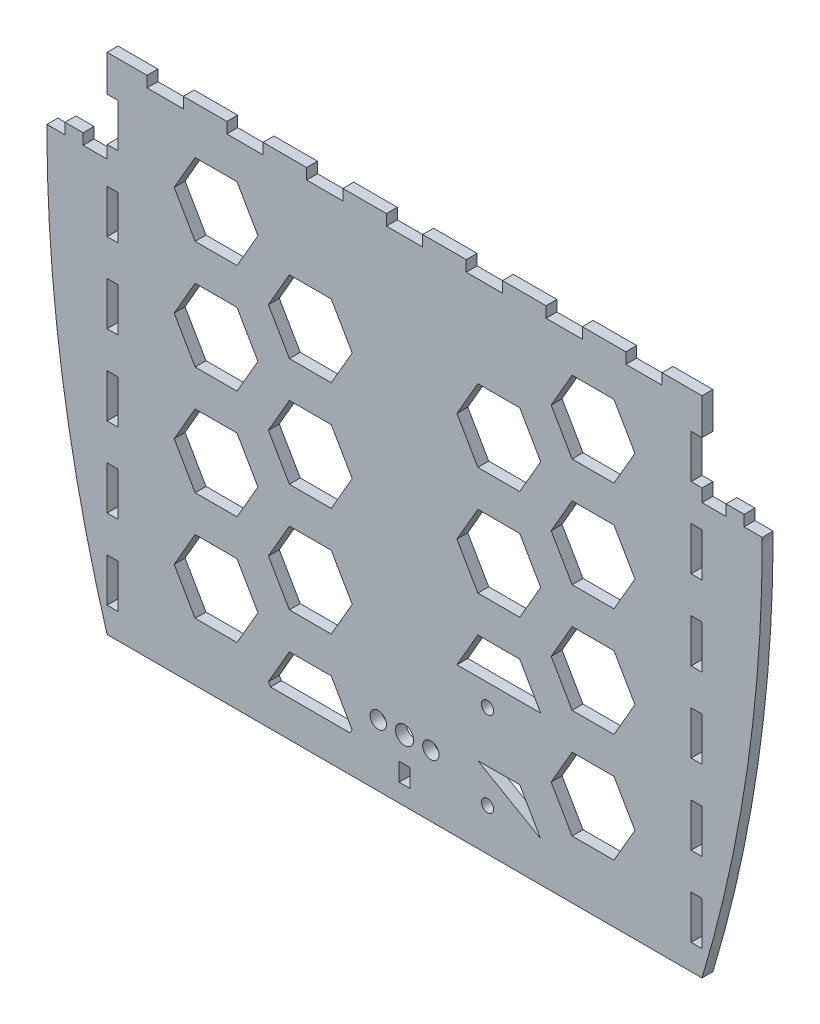
SolidWorks part; units mm, degrees
material "birch 3mm plywood"
ref_plane "Front Plane" through (0, 0, 0) normal (0, 0, 1) x (1, 0, 0)
ref_plane "Top Plane" through (0, 0, 0) normal (0, 1, 0) x (1, 0, 0)
ref_plane "Right Plane" through (0, 0, 0) normal (1, 0, 0) x (0, 0, -1)
sketch "Sketch1" plane through (0, 0, 152) normal (0, 0, 1) x (1, 0, 0)
  line L1 (-82, 69.5) -> (82, 69.5)
  line L2 (-82, 69.5) -> (-82, 44)
  line L3 (-82, -69.5) -> (82, -69.5)
  line L4 (82, 69.5) -> (82, 44)
  line L8 (-88.6, 47) -> (-93.6, 47)
  line L9 (-98.6, 44) -> (-98.6, 43.3771)
  line L12 (75, -62.5) -> (-75, -62.5) construction
  line L13 (75, 62.5) -> (75, -62.5) construction
  line L14 (-75, -62.5) -> (-75, 62.5) construction
  line L15 (-75, 62.5) -> (75, 62.5) construction
  line L33 (-93.6, 47) -> (-93.6, 44)
  line L34 (-93.6, 44) -> (-98.6, 44)
  line L35 (-88.6, 47) -> (-88.6, 44)
  line L36 (-88.6, 44) -> (-82, 44)
  line L37 (98.6, 44) -> (98.6, 43.3771)
  line L38 (93.6, 44) -> (98.6, 44)
  line L39 (93.6, 47) -> (93.6, 44)
  line L40 (88.6, 47) -> (93.6, 47)
  line L41 (88.6, 47) -> (88.6, 44)
  line L42 (88.6, 44) -> (82, 44)
  arc A12 (-98.6, 43.3771) -> (-82, -69.5) centre (293.4723, 43.3771) ccw
  arc A14 (98.6, 43.3771) -> (82, -69.5) centre (-293.4723, 43.3771) cw
  dimension "D3" = 7
  dimension "D11" = 150
  dimension "D12" = 125
  dimension "D13" = 7
  dimension "D14" = 22.5
  dimension "D15" = 16.6
  dimension "D16" = 3
  dimension "D17" = 5
  dimension "D18" = 5
extrude "Boss-Extrude1" add sketch "Sketch1" along normal blind 3
sketch "Sketch2" plane through (0, 0, 155) normal (0, 0, 1) x (1, 0, 0)
  line L0 (0, 69.5) -> (0, -69.5) construction
  line L1 (17, 69.5) -> (17, 66.5)
  line L2 (-5, 69.5) -> (5, 69.5)
  line L3 (-5, 69.5) -> (-5, 66.5)
  line L4 (-82, 69.5) -> (-82, 44)
  line L5 (-82, -69.5) -> (82, -69.5)
  line L6 (82, 44) -> (82, 69.5)
  line L7 (82, 69.5) -> (-82, 69.5)
  line L8 (-82, 69.5) -> (-82, 44)
  line L9 (-82, -69.5) -> (82, -69.5)
  line L10 (82, 44) -> (82, 69.5)
  line L11 (82, 69.5) -> (-82, 69.5)
  line L12 (-5, 66.5) -> (5, 66.5)
  line L13 (5, 69.5) -> (5, 66.5)
  line L14 (17, 69.5) -> (27, 69.5)
  line L15 (27, 69.5) -> (27, 66.5)
  line L16 (17, 66.5) -> (27, 66.5)
  line L17 (39, 69.5) -> (39, 66.5)
  line L18 (39, 69.5) -> (49, 69.5)
  line L19 (49, 69.5) -> (49, 66.5)
  line L20 (39, 66.5) -> (49, 66.5)
  line L21 (61, 69.5) -> (61, 66.5)
  line L22 (61, 69.5) -> (71, 69.5)
  line L23 (71, 69.5) -> (71, 66.5)
  line L24 (61, 66.5) -> (71, 66.5)
  line L25 (-27, 69.5) -> (-27, 66.5)
  line L26 (-27, 69.5) -> (-17, 69.5)
  line L27 (-17, 69.5) -> (-17, 66.5)
  line L28 (-27, 66.5) -> (-17, 66.5)
  line L29 (-49, 69.5) -> (-49, 66.5)
  line L30 (-49, 69.5) -> (-39, 69.5)
  line L31 (-39, 69.5) -> (-39, 66.5)
  line L32 (-49, 66.5) -> (-39, 66.5)
  line L33 (-71, 69.5) -> (-71, 66.5)
  line L34 (-71, 69.5) -> (-61, 69.5)
  line L35 (-61, 69.5) -> (-61, 66.5)
  line L36 (-71, 66.5) -> (-61, 66.5)
  line L37 (-82, 37.5) -> (-82, 25.5)
  line L38 (-82, 59.5) -> (-79, 59.5)
  line L39 (-82, 59.5) -> (-82, 47.5)
  line L40 (-82, 47.5) -> (-79, 47.5)
  line L41 (-79, 59.5) -> (-79, 47.5)
  line L42 (-82, 37.5) -> (-79, 37.5)
  line L43 (-79, 37.5) -> (-79, 25.5)
  line L44 (-82, 25.5) -> (-79, 25.5)
  line L45 (-82, 15.5) -> (-82, 3.5)
  line L46 (-82, 15.5) -> (-79, 15.5)
  line L47 (-79, 15.5) -> (-79, 3.5)
  line L48 (-82, 3.5) -> (-79, 3.5)
  line L49 (-82, -6.5) -> (-82, -18.5)
  line L50 (-82, -6.5) -> (-79, -6.5)
  line L51 (-79, -6.5) -> (-79, -18.5)
  line L52 (-82, -18.5) -> (-79, -18.5)
  line L53 (-82, -28.5) -> (-82, -40.5)
  line L54 (-82, -28.5) -> (-79, -28.5)
  line L55 (-79, -28.5) -> (-79, -40.5)
  line L56 (-82, -40.5) -> (-79, -40.5)
  line L57 (-82, -50.5) -> (-82, -62.5)
  line L58 (-82, -50.5) -> (-79, -50.5)
  line L59 (-79, -50.5) -> (-79, -62.5)
  line L60 (-82, -62.5) -> (-79, -62.5)
  line L65 (82, -50.5) -> (79, -50.5)
  line L66 (79, -50.5) -> (79, -62.5)
  line L67 (82, -62.5) -> (79, -62.5)
  line L68 (82, -50.5) -> (82, -62.5)
  line L69 (82, -28.5) -> (79, -28.5)
  line L70 (79, -28.5) -> (79, -40.5)
  line L71 (82, -40.5) -> (79, -40.5)
  line L72 (82, -28.5) -> (82, -40.5)
  line L73 (82, -6.5) -> (79, -6.5)
  line L74 (79, -6.5) -> (79, -18.5)
  line L75 (82, -18.5) -> (79, -18.5)
  line L76 (82, -6.5) -> (82, -18.5)
  line L77 (82, 15.5) -> (79, 15.5)
  line L78 (79, 15.5) -> (79, 3.5)
  line L79 (82, 3.5) -> (79, 3.5)
  line L80 (82, 15.5) -> (82, 3.5)
  line L81 (82, 37.5) -> (79, 37.5)
  line L82 (79, 37.5) -> (79, 25.5)
  line L83 (82, 25.5) -> (79, 25.5)
  line L84 (82, 37.5) -> (82, 25.5)
  line L85 (82, 47.5) -> (79, 47.5)
  line L86 (79, 59.5) -> (79, 47.5)
  line L87 (82, 59.5) -> (79, 59.5)
  line L88 (82, 59.5) -> (82, 47.5)
  line L97 (-88.6, 47) -> (-93.6, 47)
  line L98 (-88.6, 47) -> (-93.6, 47)
  line L99 (-98.6, 44) -> (-98.6, 43.3771)
  line L100 (-98.6, 44) -> (-98.6, 43.3771)
  line L101 (98.6, 43.3771) -> (98.6, 44)
  line L103 (98.6, 43.3771) -> (98.6, 44)
  line L109 (-82, 44) -> (-88.6, 44)
  line L110 (-82, 44) -> (-88.6, 44)
  line L111 (-88.6, 44) -> (-88.6, 47)
  line L112 (-88.6, 44) -> (-88.6, 47)
  line L113 (-93.6, 47) -> (-93.6, 44)
  line L114 (-93.6, 47) -> (-93.6, 44)
  line L115 (-93.6, 44) -> (-98.6, 44)
  line L116 (-93.6, 44) -> (-98.6, 44)
  line L121 (98.6, 44) -> (93.6, 44)
  line L122 (98.6, 44) -> (93.6, 44)
  line L123 (93.6, 44) -> (93.6, 47)
  line L124 (93.6, 44) -> (93.6, 47)
  line L125 (93.6, 47) -> (88.6, 47)
  line L126 (93.6, 47) -> (88.6, 47)
  line L127 (88.6, 47) -> (88.6, 44)
  line L128 (88.6, 47) -> (88.6, 44)
  line L129 (88.6, 44) -> (82, 44)
  line L130 (88.6, 44) -> (82, 44)
  arc A2 (-98.6, 43.3771) -> (-82, -69.5) centre (293.4723, 43.3771) ccw
  arc A3 (-98.6, 43.3771) -> (-82, -69.5) centre (293.4723, 43.3771) ccw
  arc A4 (82, -69.5) -> (98.6, 43.3771) centre (-293.4723, 43.3771) ccw
  arc A6 (82, -69.5) -> (98.6, 43.3771) centre (-293.4723, 43.3771) ccw
  point P10 (0, 66.5)
  line M64 (82, 44) -> (82, 69.5)
  line M65 (82, 69.5) -> (-82, 69.5)
  dimension "D2" = 10
  dimension "D3" = 3
  dimension "D6" = 12
  dimension "D7" = 12
  dimension "D8" = 3
  dimension "D9" = 12
  dimension "D10" = 10
  dimension "D12" = 10
  dimension "D1" = 0
  dimension "D4" = 4
  dimension "D5" = 4
  dimension "D11" = 6
extrude "Cut-Extrude1" cut sketch "Sketch2" against normal blind 10 contours L8 L44 L43 L42 | L33 L36 L35 L11 | L29 L32 L31 M65 | L25 L28 L27 L11 | L0 L12 L13 M65 | L0 L11 L3 L12 | L1 L16 L15 L11 | L17 L20 L19 L11 | L21 L24 L23 L11 | L87 L86 L85 M64 | L79 L77 L78 M64 | L75 L10 L73 L74 | L71 L69 L70 M64 | L67 L10 L65 L66 | L41 L40 L39 L38 | L47 L48 L45 L46 | L51 L52 L49 L50 | L55 L56 L53 L54 | L59 L60 L57 L58 | L82 L83 L84 L81
sketch "Sketch3" plane through (0, 0, 155) normal (0, 0, 1) x (1, 0, 0)
  line L0 (-49, 66.5) -> (-39, 66.5) construction
  line L1 (-45.906, 46.5) -> (-51.6795, 56.5)
  line L2 (-51.6795, 56.5) -> (-63.2265, 56.5)
  line L3 (-63.2265, 56.5) -> (-69, 46.5)
  line L4 (-69, 46.5) -> (-63.2265, 36.5)
  line L5 (-63.2265, 36.5) -> (-51.6795, 36.5)
  line L6 (-51.6795, 36.5) -> (-45.906, 46.5)
  line L7 (-79, 37.5) -> (-79, 25.5) construction
  line L8 (-19.9252, 31.5) -> (-25.6987, 41.5)
  line L9 (-25.6987, 41.5) -> (-37.2457, 41.5)
  line L10 (-37.2457, 41.5) -> (-43.0192, 31.5)
  line L11 (-43.0192, 31.5) -> (-37.2457, 21.5)
  line L12 (-37.2457, 21.5) -> (-25.6987, 21.5)
  line L13 (-25.6987, 21.5) -> (-19.9252, 31.5)
  line L16 (-13.2265, 56.5) -> (-19, 46.5)
  line L17 (-19, 46.5) -> (-13.2265, 36.5)
  line L18 (-13.2265, 36.5) -> (-10, 36.5)
  line L20 (30.0748, 31.5) -> (24.3013, 41.5)
  line L21 (24.3013, 41.5) -> (12.7543, 41.5)
  line L22 (12.7543, 41.5) -> (10, 36.7295)
  line L23 (10, 26.2705) -> (12.7543, 21.5)
  line L24 (12.7543, 21.5) -> (24.3013, 21.5)
  line L25 (24.3013, 21.5) -> (30.0748, 31.5)
  line L26 (54.094, 46.5) -> (48.3205, 56.5)
  line L27 (48.3205, 56.5) -> (36.7735, 56.5)
  line L28 (36.7735, 56.5) -> (31, 46.5)
  line L29 (31, 46.5) -> (36.7735, 36.5)
  line L30 (36.7735, 36.5) -> (48.3205, 36.5)
  line L31 (48.3205, 36.5) -> (54.094, 46.5)
  line L33 (68.5278, 41.5) -> (62.7543, 41.5)
  line L34 (62.7543, 41.5) -> (56.9808, 31.5)
  line L35 (56.9808, 31.5) -> (62.7543, 21.5)
  line L36 (62.7543, 21.5) -> (68.5278, 21.5)
  line L39 (-10, 26.5) -> (-13.2265, 26.5)
  line L40 (-13.2265, 26.5) -> (-19, 16.5)
  line L41 (-19, 16.5) -> (-13.2265, 6.5)
  line L42 (-13.2265, 6.5) -> (-10, 6.5)
  line L44 (30.0748, 1.5) -> (24.3013, 11.5)
  line L45 (24.3013, 11.5) -> (12.7543, 11.5)
  line L46 (12.7543, 11.5) -> (10, 6.7295)
  line L47 (10, -3.7295) -> (12.7543, -8.5)
  line L48 (12.7543, -8.5) -> (24.3013, -8.5)
  line L49 (24.3013, -8.5) -> (30.0748, 1.5)
  line L50 (54.094, 16.5) -> (48.3205, 26.5)
  line L51 (48.3205, 26.5) -> (36.7735, 26.5)
  line L52 (36.7735, 26.5) -> (31, 16.5)
  line L53 (31, 16.5) -> (36.7735, 6.5)
  line L54 (36.7735, 6.5) -> (48.3205, 6.5)
  line L55 (48.3205, 6.5) -> (54.094, 16.5)
  line L57 (68.5278, 11.5) -> (62.7543, 11.5)
  line L58 (62.7543, 11.5) -> (56.9808, 1.5)
  line L59 (56.9808, 1.5) -> (62.7543, -8.5)
  line L60 (62.7543, -8.5) -> (68.5278, -8.5)
  line L64 (-13.2265, -3.5) -> (-19, -13.5)
  line L65 (-19, -13.5) -> (-13.2265, -23.5)
  line L66 (-13.2265, -23.5) -> (-10, -23.5)
  line L68 (30.0748, -28.5) -> (24.3013, -18.5)
  line L69 (24.3013, -18.5) -> (12.7543, -18.5)
  line L70 (12.7543, -18.5) -> (10, -23.2705)
  line L71 (10, -33.7295) -> (12.7543, -38.5)
  line L72 (12.7543, -38.5) -> (24.3013, -38.5)
  line L73 (24.3013, -38.5) -> (30.0748, -28.5)
  line L74 (54.094, -13.5) -> (48.3205, -3.5)
  line L75 (48.3205, -3.5) -> (36.7735, -3.5)
  line L76 (36.7735, -3.5) -> (31, -13.5)
  line L77 (31, -13.5) -> (36.7735, -23.5)
  line L78 (36.7735, -23.5) -> (48.3205, -23.5)
  line L79 (48.3205, -23.5) -> (54.094, -13.5)
  line L81 (68.5278, -18.5) -> (62.7543, -18.5)
  line L82 (62.7543, -18.5) -> (56.9808, -28.5)
  line L83 (56.9808, -28.5) -> (62.7543, -38.5)
  line L84 (62.7543, -38.5) -> (68.5278, -38.5)
  line L88 (-13.2265, -33.5) -> (-19, -43.5)
  line L89 (-19, -43.5) -> (-13.2265, -53.5)
  line L90 (-13.2265, -53.5) -> (-10, -53.5)
  line L92 (30.0748, -58.5) -> (24.3013, -48.5)
  line L93 (24.3013, -48.5) -> (12.7543, -48.5)
  line L94 (12.7543, -48.5) -> (10, -53.2705)
  line L98 (54.094, -43.5) -> (48.3205, -33.5)
  line L99 (48.3205, -33.5) -> (36.7735, -33.5)
  line L100 (36.7735, -33.5) -> (31, -43.5)
  line L101 (31, -43.5) -> (36.7735, -53.5)
  line L102 (36.7735, -53.5) -> (48.3205, -53.5)
  line L103 (48.3205, -53.5) -> (54.094, -43.5)
  line L105 (68.5278, -48.5) -> (62.7543, -48.5)
  line L106 (62.7543, -48.5) -> (56.9808, -58.5)
  line L134 (-45.906, 16.5) -> (-51.6795, 26.5)
  line L135 (-51.6795, 26.5) -> (-63.2265, 26.5)
  line L136 (-63.2265, 26.5) -> (-69, 16.5)
  line L137 (-69, 16.5) -> (-63.2265, 6.5)
  line L138 (-63.2265, 6.5) -> (-51.6795, 6.5)
  line L139 (-51.6795, 6.5) -> (-45.906, 16.5)
  line L140 (-19.9252, 1.5) -> (-25.6987, 11.5)
  line L141 (-25.6987, 11.5) -> (-37.2457, 11.5)
  line L142 (-37.2457, 11.5) -> (-43.0192, 1.5)
  line L143 (-43.0192, 1.5) -> (-37.2457, -8.5)
  line L144 (-37.2457, -8.5) -> (-25.6987, -8.5)
  line L145 (-25.6987, -8.5) -> (-19.9252, 1.5)
  line L146 (-45.906, -13.5) -> (-51.6795, -3.5)
  line L147 (-51.6795, -3.5) -> (-63.2265, -3.5)
  line L148 (-63.2265, -3.5) -> (-69, -13.5)
  line L149 (-69, -13.5) -> (-63.2265, -23.5)
  line L150 (-63.2265, -23.5) -> (-51.6795, -23.5)
  line L151 (-51.6795, -23.5) -> (-45.906, -13.5)
  line L152 (-19.9252, -28.5) -> (-25.6987, -18.5)
  line L153 (-25.6987, -18.5) -> (-37.2457, -18.5)
  line L154 (-37.2457, -18.5) -> (-43.0192, -28.5)
  line L155 (-43.0192, -28.5) -> (-37.2457, -38.5)
  line L156 (-37.2457, -38.5) -> (-25.6987, -38.5)
  line L157 (-25.6987, -38.5) -> (-19.9252, -28.5)
  line L158 (-45.906, -43.5) -> (-51.6795, -33.5)
  line L159 (-51.6795, -33.5) -> (-63.2265, -33.5)
  line L160 (-63.2265, -33.5) -> (-69, -43.5)
  line L161 (-69, -43.5) -> (-63.2265, -53.5)
  line L162 (-63.2265, -53.5) -> (-51.6795, -53.5)
  line L163 (-51.6795, -53.5) -> (-45.906, -43.5)
  line L164 (-19.9252, -58.5) -> (-25.6987, -48.5)
  line L165 (-25.6987, -48.5) -> (-37.2457, -48.5)
  line L166 (-37.2457, -48.5) -> (-43.0192, -58.5)
  line L185 (-40, 56.5) -> (-37.2457, 51.7295)
  line L186 (-37.2457, 51.7295) -> (-25.6987, 51.7295)
  line L187 (-25.6987, 51.7295) -> (-22.9445, 56.5)
  line L188 (31, -73.5) -> (36.7735, -83.5) [skipped]
  line L189 (36.7735, -83.5) -> (48.3205, -83.5) [skipped]
  line L190 (48.3205, -83.5) -> (54.094, -73.5) [skipped]
  line L191 (80.0748, -88.5) -> (74.3013, -78.5) [skipped]
  line L192 (74.3013, -78.5) -> (62.7543, -78.5) [skipped]
  line L193 (62.7543, -78.5) -> (56.9808, -88.5) [skipped]
  line L194 (56.9808, -88.5) -> (62.7543, -98.5) [skipped]
  line L195 (62.7543, -98.5) -> (74.3013, -98.5) [skipped]
  line L196 (74.3013, -98.5) -> (80.0748, -88.5) [skipped]
  line L197 (54.094, -73.5) -> (48.3205, -63.5) [skipped]
  line L198 (48.3205, -63.5) -> (36.7735, -63.5) [skipped]
  line L199 (36.7735, -63.5) -> (31, -73.5) [skipped]
  line L200 (-1.6795, -83.5) -> (4.094, -73.5) [skipped]
  line L201 (30.0748, -88.5) -> (24.3013, -78.5) [skipped]
  line L202 (24.3013, -78.5) -> (12.7543, -78.5) [skipped]
  line L203 (12.7543, -78.5) -> (6.9808, -88.5) [skipped]
  line L204 (6.9808, -88.5) -> (12.7543, -98.5) [skipped]
  line L205 (12.7543, -98.5) -> (24.3013, -98.5) [skipped]
  line L206 (24.3013, -98.5) -> (30.0748, -88.5) [skipped]
  line L207 (4.094, -73.5) -> (-1.6795, -63.5) [skipped]
  line L208 (-1.6795, -63.5) -> (-13.2265, -63.5) [skipped]
  line L209 (-13.2265, -63.5) -> (-19, -73.5) [skipped]
  line L210 (-19, -73.5) -> (-13.2265, -83.5) [skipped]
  line L211 (-13.2265, -83.5) -> (-1.6795, -83.5) [skipped]
  line L212 (-19.9252, -88.5) -> (-25.6987, -78.5) [skipped]
  line L213 (-25.6987, -78.5) -> (-37.2457, -78.5) [skipped]
  line L214 (-37.2457, -78.5) -> (-43.0192, -88.5) [skipped]
  line L215 (-43.0192, -88.5) -> (-37.2457, -98.5) [skipped]
  line L216 (-37.2457, -98.5) -> (-25.6987, -98.5) [skipped]
  line L217 (-25.6987, -98.5) -> (-19.9252, -88.5) [skipped]
  line L218 (-45.906, -73.5) -> (-51.6795, -63.5) [skipped]
  line L219 (-51.6795, -63.5) -> (-63.2265, -63.5) [skipped]
  line L220 (-63.2265, -63.5) -> (-69, -73.5) [skipped]
  line L221 (-69, -73.5) -> (-63.2265, -83.5) [skipped]
  line L222 (-63.2265, -83.5) -> (-51.6795, -83.5) [skipped]
  line L223 (-51.6795, -83.5) -> (-45.906, -73.5) [skipped]
  line L224 (-40, 56.5) -> (-22.9445, 56.5)
  line L225 (24.3013, 51.7295) -> (27.0555, 56.5)
  line L226 (-25.6987, 71.7295) -> (-37.2457, 71.7295) [skipped]
  line L227 (-19.9252, 61.7295) -> (-25.6987, 71.7295) [skipped]
  line L228 (-37.2457, 71.7295) -> (-43.0192, 61.7295) [skipped]
  line L229 (10, 56.5) -> (27.0555, 56.5)
  line L230 (12.7543, 51.7295) -> (24.3013, 51.7295)
  line L231 (10, 56.5) -> (12.7543, 51.7295)
  line L233 (60, 56.5) -> (68.5278, 56.5)
  line L234 (62.7543, 51.7295) -> (68.5278, 51.7295)
  line L235 (60, 56.5) -> (62.7543, 51.7295)
  line L236 (68.5278, 56.5) -> (68.5278, 51.7295)
  line L237 (68.5278, 41.5) -> (68.5278, 21.5)
  line L238 (68.5278, 11.5) -> (68.5278, -8.5)
  line L239 (68.5278, -18.5) -> (68.5278, -38.5)
  line L240 (68.5278, -48.5) -> (68.5278, -58.5)
  line L241 (56.9808, -58.5) -> (68.5278, -58.5)
  line L243 (-43.0192, -58.5) -> (-19.9252, -58.5)
  line L244 (0, -69.5) -> (0, 66.5) construction
  line L245 (74.3013, 51.7295) -> (77.0555, 56.5) [skipped]
  line L246 (80.0748, -58.5) -> (74.3013, -48.5) [skipped]
  line L247 (74.3013, -68.5) -> (80.0748, -58.5) [skipped]
  line L248 (62.7543, -68.5) -> (74.3013, -68.5) [skipped]
  line L249 (56.9808, -58.5) -> (62.7543, -68.5) [skipped]
  line L250 (74.3013, -38.5) -> (80.0748, -28.5) [skipped]
  line L251 (80.0748, -28.5) -> (74.3013, -18.5) [skipped]
  line L252 (74.3013, -8.5) -> (80.0748, 1.5) [skipped]
  line L253 (80.0748, 1.5) -> (74.3013, 11.5) [skipped]
  line L254 (80.0748, 31.5) -> (74.3013, 41.5) [skipped]
  line L255 (74.3013, 21.5) -> (80.0748, 31.5) [skipped]
  line L256 (6.9808, -58.5) -> (12.7543, -68.5) [skipped]
  line L257 (12.7543, -68.5) -> (24.3013, -68.5) [skipped]
  line L258 (24.3013, -68.5) -> (30.0748, -58.5) [skipped]
  line L259 (-25.6987, -68.5) -> (-19.9252, -58.5) [skipped]
  line L260 (-43.0192, -58.5) -> (-37.2457, -68.5) [skipped]
  line L261 (-37.2457, -68.5) -> (-25.6987, -68.5) [skipped]
  line L262 (-82, -69.5) -> (82, -69.5) construction
  line L263 (-5, 66.5) -> (5, 66.5) construction
  line L264 (-10, -53.5) -> (-10, -33.5)
  line L265 (-5, 69.5) -> (-17, 69.5) construction
  line L266 (-10, 69.5) -> (10, 69.5)
  line L267 (10, 69.5) -> (10, 56.5)
  line L269 (-10, -3.5) -> (-13.2265, -3.5)
  line L270 (-69, 46.5) -> (-51.6795, 36.5) construction
  line L271 (-10, -33.5) -> (-13.2265, -33.5)
  line L272 (-10, -23.5) -> (-10, -3.5)
  line L273 (-10, 6.5) -> (-10, 26.5)
  line L274 (-1.6795, -3.5) -> (-7.453, -3.5) [skipped]
  line L275 (-10, 36.5) -> (-10, 56.5)
  line L277 (-10, 56.5) -> (-13.2265, 56.5)
  line L278 (10, -58.5) -> (30.0748, -58.5)
  line L279 (10, -23.2705) -> (10, -33.7295)
  line L280 (10, -53.2705) -> (10, -58.5)
  line L283 (10, 36.7295) -> (10, 26.2705)
  line L284 (10, -53.7295) -> (9.8675, -53.5) [skipped]
  line L285 (-1.6795, 56.5) -> (-7.453, 56.5) [skipped]
  line L286 (-1.6795, -33.5) -> (-7.453, -33.5) [skipped]
  line L287 (4.094, 46.5) -> (-1.6795, 56.5) [skipped]
  line L288 (-1.6795, 36.5) -> (4.094, 46.5) [skipped]
  line L289 (4.094, 16.5) -> (-1.6795, 26.5) [skipped]
  line L290 (-1.6795, 6.5) -> (4.094, 16.5) [skipped]
  line L291 (4.094, -13.5) -> (-1.6795, -3.5) [skipped]
  line L292 (-1.6795, -23.5) -> (4.094, -13.5) [skipped]
  line L293 (-1.6795, -53.5) -> (4.094, -43.5) [skipped]
  circle A0 centre (-57.453, 46.5) radius 10 construction
  circle A1 centre (-31.4722, 31.5) radius 10 construction
  arc A3 (10, 26.2772) -> (10, 36.7228) centre (18.5278, 31.5) ccw construction
  circle A4 centre (42.547, 46.5) radius 10 construction
  circle A5 centre (68.5278, 31.5) radius 10 construction
  arc A6 (-10, 26.1702) -> (-10, 6.8298) centre (-7.453, 16.5) ccw construction
  circle A8 centre (42.547, 16.5) radius 10 construction
  circle A9 centre (68.5278, 1.5) radius 10 construction
  arc A10 (-10, -3.8298) -> (-10, -23.1702) centre (-7.453, -13.5) ccw construction
  arc A11 (10, -33.7228) -> (10, -23.2772) centre (18.5278, -28.5) ccw construction
  circle A12 centre (42.547, -13.5) radius 10 construction
  circle A13 centre (68.5278, -28.5) radius 10 construction
  arc A15 (28.5278, -58.5) -> (10, -53.2772) centre (18.5278, -58.5) ccw construction
  circle A16 centre (42.547, -43.5) radius 10 construction
  circle A17 centre (68.5278, -58.5) radius 10 construction
  circle A18 centre (18.5278, 61.7295) radius 10 construction
  circle A19 centre (68.5278, 61.7295) radius 10 construction
  circle A22 centre (-57.453, 16.5) radius 10 construction
  circle A23 centre (-31.4722, 1.5) radius 10 construction
  circle A24 centre (-57.453, -13.5) radius 10 construction
  circle A25 centre (-31.4722, -28.5) radius 10 construction
  circle A26 centre (-57.453, -43.5) radius 10 construction
  circle A27 centre (-31.4722, -58.5) radius 10 construction
  arc A28 (-10, -33.8298) -> (-10, -53.1702) centre (-7.453, -43.5) ccw construction
  arc A29 (-10, 56.1702) -> (-10, 36.8298) centre (-7.453, 46.5) ccw construction
  circle A30 centre (-31.4722, 61.7295) radius 10 construction
  circle A31 centre (42.547, -73.5) radius 10 construction
  circle A32 centre (68.5278, -88.5) radius 10 construction
  circle A33 centre (-7.453, -73.5) radius 10 construction
  circle A34 centre (18.5278, -88.5) radius 10 construction
  circle A35 centre (-31.4722, -88.5) radius 10 construction
  circle A36 centre (-57.453, -73.5) radius 10 construction
  arc A37 (-7.453, 36.5) -> (-7.453, 56.5) centre (-7.453, 46.5) ccw construction
  arc A38 (0, -50.1673) -> (-7.453, -33.5) centre (-7.453, -43.5) ccw construction
  arc A39 (10, -3.7228) -> (10, 6.7228) centre (18.5278, 1.5) ccw construction
  dimension "D3" = 20
  dimension "D1" = 10
  dimension "D2" = 10
  dimension "D9" = 10
  dimension "D4" = 2
  dimension "D5" = 3
  dimension "D6" = 5
  dimension "D7" = 2
  dimension "D8" = 3
sketch "Sketch4" plane through (0, 0, 155) normal (0, 0, 1) x (1, 0, 0)
  line L4 (-1.5, -59.5) -> (-1.5, -64.5)
  line L5 (1.5, -59.5) -> (-1.5, -59.5)
  line L6 (1.5, -64.5) -> (1.5, -59.5)
  line L7 (-1.5, -64.5) -> (1.5, -64.5)
  line L8 (-1.5, -59.5) -> (-1.5, -64.5)
  line L9 (1.5, -59.5) -> (-1.5, -59.5)
  line L10 (1.5, -64.5) -> (1.5, -59.5)
  line L11 (-1.5, -64.5) -> (1.5, -64.5)
  circle A0 centre (22.8668, -34.5) radius 1.7 construction
  circle A1 centre (22.8668, -57.9) radius 1.7 construction
  circle A2 centre (22.8668, -34.5) radius 1.7
  circle A3 centre (22.8668, -57.9) radius 1.7
  dimension "D1" = 0
sketch "Sketch5" plane through (0, 0, 155) normal (0, 0, 1) x (1, 0, 0)
  line L0 (-10, -59.5) -> (-10, 56.5) construction
  line L1 (24.3013, 41.5) -> (12.7543, 41.5) construction
  line L2 (10, 56.5) -> (10, -59.5) construction
  line L3 (0, -69.5) -> (0, 66.5) construction
  line L4 (-82, -69.5) -> (82, -69.5) construction
  line L5 (11.547, 46.5) -> (5.7735, 56.5) construction
  line L6 (5.7735, 56.5) -> (-5.7735, 56.5) construction
  line L7 (-5.7735, 56.5) -> (-11.547, 46.5) construction
  line L8 (-11.547, 46.5) -> (-5.7735, 36.5) construction
  line L9 (-5.7735, 36.5) -> (5.7735, 36.5) construction
  line L10 (5.7735, 36.5) -> (11.547, 46.5) construction
  line L11 (11.547, 16.5) -> (5.7735, 26.5) construction
  line L12 (63.5085, 46.5) -> (57.735, 56.5)
  line L13 (57.735, 56.5) -> (46.188, 56.5)
  line L14 (46.188, 56.5) -> (40.4145, 46.5)
  line L15 (40.4145, 46.5) -> (46.188, 36.5)
  line L16 (46.188, 36.5) -> (57.735, 36.5)
  line L17 (57.735, 36.5) -> (63.5085, 46.5)
  line L18 (31.7543, 41.5) -> (20.2073, 41.5)
  line L19 (20.2073, 41.5) -> (14.4338, 31.5)
  line L20 (14.4338, 31.5) -> (20.2073, 21.5)
  line L21 (20.2073, 21.5) -> (31.7543, 21.5)
  line L22 (31.7543, 21.5) -> (37.5278, 31.5)
  line L23 (37.5278, 31.5) -> (31.7543, 41.5)
  line L24 (-20.2073, 41.5) -> (-31.7543, 41.5)
  line L25 (-31.7543, 41.5) -> (-37.5278, 31.5)
  line L26 (-37.5278, 31.5) -> (-31.7543, 21.5)
  line L27 (-31.7543, 21.5) -> (-20.2073, 21.5)
  line L28 (-20.2073, 21.5) -> (-14.4338, 31.5)
  line L29 (-14.4338, 31.5) -> (-20.2073, 41.5)
  line L30 (11.547, 16.5) -> (5.7735, 26.5) construction
  line L31 (5.7735, 26.5) -> (-5.7735, 26.5) construction
  line L32 (-5.7735, 26.5) -> (-11.547, 16.5) construction
  line L33 (-11.547, 16.5) -> (-5.7735, 6.5) construction
  line L34 (-5.7735, 6.5) -> (5.7735, 6.5) construction
  line L35 (5.7735, 6.5) -> (11.547, 16.5) construction
  line L36 (5.7735, 26.5) -> (-5.7735, 26.5) construction
  line L37 (-5.7735, 26.5) -> (-11.547, 16.5) construction
  line L38 (-11.547, 16.5) -> (-5.7735, 6.5) construction
  line L39 (-5.7735, 6.5) -> (5.7735, 6.5) construction
  line L40 (5.7735, 6.5) -> (11.547, 16.5) construction
  line L41 (-20.2073, 11.5) -> (-31.7543, 11.5)
  line L42 (-31.7543, 11.5) -> (-37.5278, 1.5)
  line L43 (-37.5278, 1.5) -> (-31.7543, -8.5)
  line L44 (-31.7543, -8.5) -> (-20.2073, -8.5)
  line L45 (-20.2073, -8.5) -> (-14.4338, 1.5)
  line L46 (-14.4338, 1.5) -> (-20.2073, 11.5)
  line L47 (31.7543, 11.5) -> (20.2073, 11.5)
  line L48 (20.2073, 11.5) -> (14.4338, 1.5)
  line L49 (14.4338, 1.5) -> (20.2073, -8.5)
  line L50 (20.2073, -8.5) -> (31.7543, -8.5)
  line L51 (31.7543, -8.5) -> (37.5278, 1.5)
  line L52 (37.5278, 1.5) -> (31.7543, 11.5)
  line L53 (63.5085, 16.5) -> (57.735, 26.5)
  line L54 (57.735, 26.5) -> (46.188, 26.5)
  line L55 (46.188, 26.5) -> (40.4145, 16.5)
  line L56 (40.4145, 16.5) -> (46.188, 6.5)
  line L57 (46.188, 6.5) -> (57.735, 6.5)
  line L58 (57.735, 6.5) -> (63.5085, 16.5)
  line L59 (11.547, -13.5) -> (5.7735, -3.5) construction
  line L60 (5.7735, -3.5) -> (-5.7735, -3.5) construction
  line L61 (-5.7735, -3.5) -> (-11.547, -13.5) construction
  line L62 (-11.547, -13.5) -> (-5.7735, -23.5) construction
  line L63 (-5.7735, -23.5) -> (5.7735, -23.5) construction
  line L64 (5.7735, -23.5) -> (11.547, -13.5) construction
  line L65 (-20.2073, -18.5) -> (-31.7543, -18.5)
  line L66 (-31.7543, -18.5) -> (-37.5278, -28.5)
  line L67 (-37.5278, -28.5) -> (-31.7543, -38.5)
  line L68 (-31.7543, -38.5) -> (-20.2073, -38.5)
  line L69 (-20.2073, -38.5) -> (-14.4338, -28.5)
  line L70 (-14.4338, -28.5) -> (-20.2073, -18.5)
  line L71 (31.7543, -18.5) -> (20.2073, -18.5)
  line L72 (20.2073, -18.5) -> (14.4338, -28.5)
  line L76 (37.5278, -28.5) -> (31.7543, -18.5)
  line L77 (63.5085, -13.5) -> (57.735, -3.5)
  line L78 (57.735, -3.5) -> (46.188, -3.5)
  line L79 (46.188, -3.5) -> (40.4145, -13.5)
  line L80 (40.4145, -13.5) -> (46.188, -23.5)
  line L81 (46.188, -23.5) -> (57.735, -23.5)
  line L82 (57.735, -23.5) -> (63.5085, -13.5)
  line L83 (11.547, -43.5) -> (5.7735, -33.5) construction
  line L84 (5.7735, -33.5) -> (-5.7735, -33.5) construction
  line L85 (-5.7735, -33.5) -> (-11.547, -43.5) construction
  line L86 (-11.547, -43.5) -> (-5.7735, -53.5) construction
  line L87 (-5.7735, -53.5) -> (5.7735, -53.5) construction
  line L88 (5.7735, -53.5) -> (11.547, -43.5) construction
  line L89 (-20.2073, -48.5) -> (-31.7543, -48.5)
  line L90 (-31.7543, -48.5) -> (-37.5278, -58.5)
  line L91 (-37.5278, -58.5) -> (-36.9504, -59.5)
  line L93 (-15.0111, -59.5) -> (-14.4338, -58.5)
  line L94 (-14.4338, -58.5) -> (-20.2073, -48.5)
  line L95 (31.7543, -48.5) -> (20.2073, -48.5)
  line L100 (37.5278, -58.5) -> (31.7543, -48.5)
  line L101 (63.5085, -43.5) -> (57.735, -33.5)
  line L102 (57.735, -33.5) -> (46.188, -33.5)
  line L103 (46.188, -33.5) -> (40.4145, -43.5)
  line L104 (40.4145, -43.5) -> (46.188, -53.5)
  line L105 (46.188, -53.5) -> (57.735, -53.5)
  line L106 (57.735, -53.5) -> (63.5085, -43.5)
  line L107 (11.547, 46.5) -> (11.547, 16.5) construction
  line L108 (-40.413, 46.5) -> (-46.1865, 56.5)
  line L109 (-46.1865, 56.5) -> (-57.7335, 56.5)
  line L110 (-57.7335, 56.5) -> (-63.507, 46.5)
  line L111 (-63.507, 46.5) -> (-57.7335, 36.5)
  line L112 (-57.7335, 36.5) -> (-46.1865, 36.5)
  line L113 (-46.1865, 36.5) -> (-40.413, 46.5)
  line L114 (-40.413, 16.5) -> (-46.1865, 26.5)
  line L115 (-46.1865, 26.5) -> (-57.7335, 26.5)
  line L116 (-57.7335, 26.5) -> (-63.507, 16.5)
  line L117 (-63.507, 16.5) -> (-57.7335, 6.5)
  line L118 (-57.7335, 6.5) -> (-46.1865, 6.5)
  line L119 (-46.1865, 6.5) -> (-40.413, 16.5)
  line L120 (-40.413, -13.5) -> (-46.1865, -3.5)
  line L121 (-46.1865, -3.5) -> (-57.7335, -3.5)
  line L122 (-57.7335, -3.5) -> (-63.507, -13.5)
  line L123 (-63.507, -13.5) -> (-57.7335, -23.5)
  line L124 (-57.7335, -23.5) -> (-46.1865, -23.5)
  line L125 (-46.1865, -23.5) -> (-40.413, -13.5)
  line L126 (-40.413, -43.5) -> (-46.1865, -33.5)
  line L127 (-46.1865, -33.5) -> (-57.7335, -33.5)
  line L128 (-57.7335, -33.5) -> (-63.507, -43.5)
  line L129 (-63.507, -43.5) -> (-57.7335, -53.5)
  line L130 (-57.7335, -53.5) -> (-46.1865, -53.5)
  line L131 (-46.1865, -53.5) -> (-40.413, -43.5)
  line L156 (11.547, 46.5) -> (-40.413, 46.5) construction
  line L205 (14.4338, -28.5) -> (37.5278, -28.5)
  line L218 (-20.2073, 41.5) -> (-20.2073, 71.5) construction
  line L225 (11.547, -73.339) -> (5.7735, -63.339) construction
  line L226 (5.7735, -63.339) -> (-5.7735, -63.339) construction
  line L227 (-5.7735, -63.339) -> (-11.547, -73.339) construction
  line L228 (-11.547, -73.339) -> (-5.7735, -83.339) construction
  line L229 (-5.7735, -83.339) -> (5.7735, -83.339) construction
  line L230 (5.7735, -83.339) -> (11.547, -73.339) construction
  line L237 (-40.413, -43.5) -> (-40.413, -73.5) construction
  line L238 (-15.0111, -59.5) -> (-36.9504, -59.5)
  line L244 (20.2073, -48.5) -> (37.5278, -58.5)
  line L245 (-69, -59.5) -> (-69, 58.0579) construction
  line L246 (-79, 59.5) -> (-79, 47.5) construction
  line L247 (-72.1673, 41.5) -> (-83.7143, 41.5) [skipped]
  line L248 (-83.7143, 41.5) -> (-89.4878, 31.5) [skipped]
  line L249 (-89.4878, 31.5) -> (-83.7143, 21.5) [skipped]
  line L250 (-83.7143, 21.5) -> (-72.1673, 21.5) [skipped]
  line L251 (-72.1673, 21.5) -> (-66.3938, 31.5) [skipped]
  line L252 (-66.3938, 31.5) -> (-72.1673, 41.5) [skipped]
  line L253 (-72.1673, 11.5) -> (-83.7143, 11.5) [skipped]
  line L254 (-83.7143, 11.5) -> (-89.4878, 1.5) [skipped]
  line L255 (-89.4878, 1.5) -> (-83.7143, -8.5) [skipped]
  line L256 (-83.7143, -8.5) -> (-72.1673, -8.5) [skipped]
  line L257 (-72.1673, -8.5) -> (-66.3938, 1.5) [skipped]
  line L258 (-66.3938, 1.5) -> (-72.1673, 11.5) [skipped]
  line L259 (-72.1673, -18.5) -> (-83.7143, -18.5) [skipped]
  line L260 (-83.7143, -18.5) -> (-89.4878, -28.5) [skipped]
  line L261 (-89.4878, -28.5) -> (-83.7143, -38.5) [skipped]
  line L262 (-83.7143, -38.5) -> (-72.1673, -38.5) [skipped]
  line L263 (-72.1673, -38.5) -> (-66.3938, -28.5) [skipped]
  line L264 (-66.3938, -28.5) -> (-72.1673, -18.5) [skipped]
  line L265 (-72.1673, -48.5) -> (-83.7143, -48.5) [skipped]
  line L266 (-83.7143, -48.5) -> (-89.4878, -58.5) [skipped]
  line L267 (-89.4878, -58.5) -> (-83.7143, -68.5) [skipped]
  line L269 (-72.1673, -68.5) -> (-66.3938, -58.5) [skipped]
  line L270 (-66.3938, -58.5) -> (-72.1673, -48.5) [skipped]
  line L271 (-40.413, -73.339) -> (-46.1865, -63.339) [skipped]
  line L272 (-46.1865, -63.339) -> (-57.7335, -63.339) [skipped]
  line L273 (-57.7335, -63.339) -> (-63.507, -73.339) [skipped]
  line L274 (-63.507, -73.339) -> (-57.7335, -83.339) [skipped]
  line L275 (-57.7335, -83.339) -> (-46.1865, -83.339) [skipped]
  line L276 (-46.1865, -83.339) -> (-40.413, -73.339) [skipped]
  line L277 (-31.7543, -68.5) -> (-20.2073, -68.5) [skipped]
  line L278 (-1.5, -64.5) -> (1.5, -64.5) construction
  line L279 (-1.5, -59.5) -> (-1.5, -64.5) construction
  line L280 (1.5, -59.5) -> (-1.5, -59.5) construction
  line L281 (1.5, -64.5) -> (1.5, -59.5) construction
  line L282 (-1.5, -64.5) -> (1.5, -64.5)
  line L283 (-1.5, -59.5) -> (-1.5, -64.5)
  line L284 (1.5, -59.5) -> (-1.5, -59.5)
  line L285 (1.5, -64.5) -> (1.5, -59.5)
  line L332 (20.2073, -68.5) -> (31.7543, -68.5) [skipped]
  line L333 (63.5085, -73.339) -> (57.735, -63.339) [skipped]
  line L334 (57.735, -63.339) -> (46.188, -63.339) [skipped]
  line L335 (46.188, -63.339) -> (40.4145, -73.339) [skipped]
  line L336 (40.4145, -73.339) -> (46.188, -83.339) [skipped]
  line L337 (46.188, -83.339) -> (57.735, -83.339) [skipped]
  line L338 (57.735, -83.339) -> (63.5085, -73.339) [skipped]
  line L344 (20.2073, -48.5) -> (14.4338, -58.5) [skipped]
  line L345 (36.9504, -59.5) -> (37.5278, -58.5) [skipped]
  line L346 (14.4338, -58.5) -> (15.0111, -59.5) [skipped]
  line L347 (14.4338, -28.5) -> (20.2073, -38.5) [skipped]
  line L348 (20.2073, -38.5) -> (31.7543, -38.5) [skipped]
  line L349 (31.7543, -38.5) -> (37.5278, -28.5) [skipped]
  circle A0 centre (0, 46.5) radius 10 construction
  circle A1 centre (51.9615, 46.5) radius 10 construction
  circle A2 centre (25.9808, 31.5) radius 10 construction
  circle A3 centre (-25.9808, 31.5) radius 10 construction
  circle A4 centre (0, 16.5) radius 10 construction
  circle A5 centre (22.8668, -57.9) radius 1.7 construction
  circle A6 centre (22.8668, -34.5) radius 1.7 construction
  circle A7 centre (22.8668, -57.9) radius 1.7
  circle A8 centre (22.8668, -34.5) radius 1.7
  dimension "D1" = 10
  dimension "D2" = 10
  dimension "D3" = 10
  dimension "D4" = 10
  dimension "D5" = 10
  dimension "D6" = 30
  dimension "D8" = 51.96
  dimension "D10" = 30
  dimension "D12" = 30
  dimension "D14" = 10
  dimension "D15" = 10
  dimension "D7" = 4
  dimension "D11" = 2
  dimension "D13" = 2
extrude "Cut-Extrude2" cut sketch "Sketch5" against normal blind 3
sketch "Sketch6" plane through (0, 0, 155) normal (0, 0, 1) x (1, 0, 0)
  line L0 (0, -69.5) -> (0, -52.5) construction
  line L1 (-82, -69.5) -> (82, -69.5) construction
  line L2 (0, -52.5) -> (7.25, -52.5) construction
  circle A0 centre (0, -52.5) radius 2.5
  circle A1 centre (-7.25, -52.5) radius 2.25
  circle A2 centre (7.25, -52.5) radius 2.25
  point P7 (0, 0)
  point P10 (0, 0)
  dimension "D1" = 4.5
  dimension "D2" = 5
  dimension "D3" = 19.5
  dimension "D4" = 2.5
extrude "Cut-Extrude3" cut sketch "Sketch6" against normal blind 10
